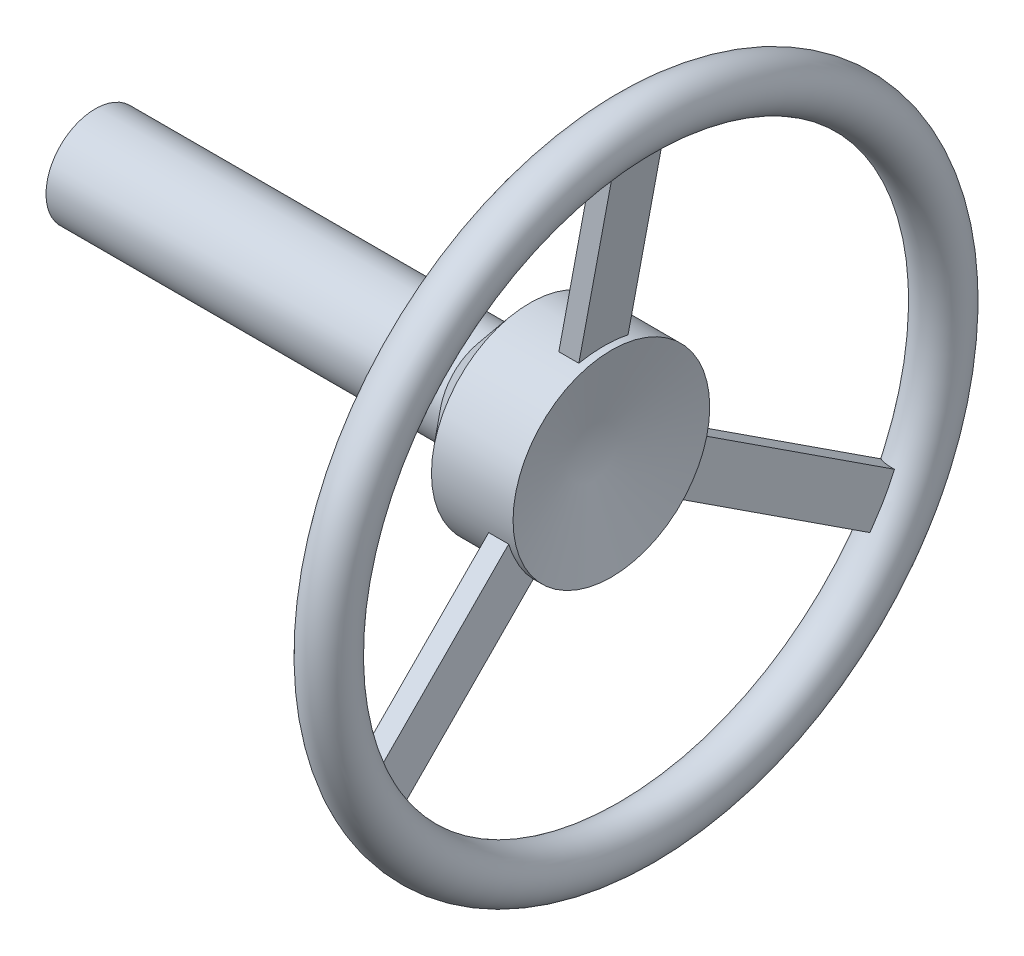
SolidWorks part; units mm, degrees
material "AISI 1015 Steel, Cold Drawn (SS)"
ref_plane "Front Plane" through (0, 0, 0) normal (0, 0, 1) x (1, 0, 0)
ref_plane "Top Plane" through (0, 0, 0) normal (0, 1, 0) x (1, 0, 0)
ref_plane "Right Plane" through (0, 0, 0) normal (1, 0, 0) x (0, 0, -1)
sketch "Sketch1" plane through (0, 0, 0) normal (0, 0, 1) x (1, 0, 0)
  line L0 (0.0204, 0) -> (0, 0) construction
  line L1 (0.0204, 0) -> (0.0204, 5)
  line L2 (0.0204, 5) -> (40.0204, 5)
  line L3 (40.0204, 5) -> (44.2159, 10)
  line L4 (44.2159, 10) -> (52.5159, 10)
  line L5 (52.5159, 10) -> (49.991, 0)
  line L6 (49.991, 0) -> (0.0204, 0)
  line L7 (49.991, 0) -> (59.9491, 0) construction
  point P3 (0.0204, 0)
  dimension "D1" = 40
  dimension "D2" = 130
  dimension "D3" = 8.3
  dimension "D4" = 5
  dimension "D5" = 10
  dimension "D6" = 75.83
  dimension "D7" = 75.83
revolve "Revolve1" add sketch "Sketch1" angle 360 about L7
sketch "Sketch2" plane through (0, 0, 0) normal (0, 0, 1) x (1, 0, 0)
  line L0 (0.0204, 5) -> (0.0204, -5) construction
  line L1 (-18.2893, 0) -> (77.0683, 0) construction
  circle A0 centre (55.0204, 31.25) radius 2.5
  dimension "D1" = 5
  dimension "D2" = 31.25
  dimension "D3" = 55
revolve "Revolve2" add sketch "Sketch2" angle 360 about L1
sketch "Sketch3" plane through (0, 0, 0) normal (0, 0, 1) x (1, 0, 0)
  line L0 (49.5813, 9.2) -> (51.6159, 9.2)
  line L1 (49.5813, 9.2) -> (54.0013, 32.8927)
  line L2 (54.0013, 32.8927) -> (56.0359, 32.8927)
  line L3 (56.0359, 32.8927) -> (51.6159, 9.2)
  line L4 (52.5159, 10) -> (52.5159, -10) construction
  line L5 (0.0204, 5) -> (0.0204, -5) construction
  point P6 (0, 0)
  dimension "D1" = 2
  dimension "D2" = 9.2
  dimension "D3" = 0.9
  dimension "D4" = 4.42
  dimension "D5" = 56.0155
extrude "Boss-Extrude1" add sketch "Sketch3" along normal mid plane 5
pattern_circular "CirPattern1" count 3 over 360 about axis through (0, 0, 0) along (1, 0, 0) of "Boss-Extrude1"
